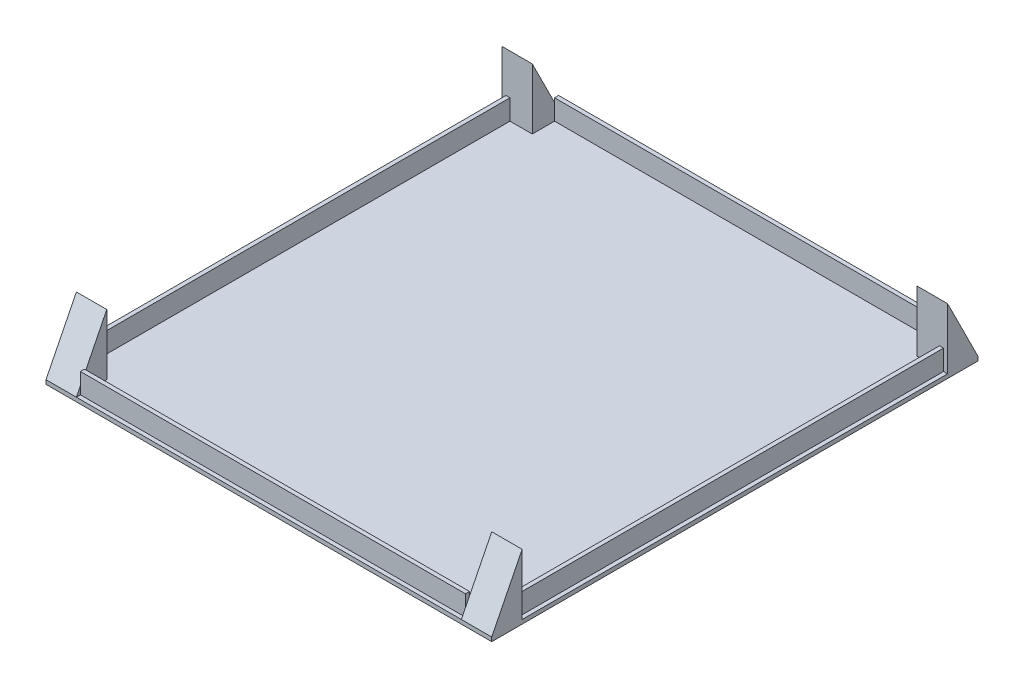
SolidWorks part; units mm, degrees
ref_plane "Front Plane" through (0, 0, 0) normal (0, 0, 1) x (1, 0, 0)
ref_plane "Top Plane" through (0, 0, 0) normal (0, 1, 0) x (1, 0, 0)
ref_plane "Right Plane" through (0, 0, 0) normal (1, 0, 0) x (0, 0, -1)
sketch "Sketch2" plane through (0, 0, 0) normal (0, 1, 0) x (1, 0, 0)
  line L1 (-110, 120) -> (110, 120)
  line L2 (-110, 120) -> (-110, -120)
  line L3 (-110, -120) -> (110, -120)
  line L4 (110, 120) -> (110, -120)
  line L5 (-110, 120) -> (110, -120) construction
  line L6 (-110, -120) -> (110, 120) construction
  point P0 (0, 0)
  dimension "D1" = 220
  dimension "D2" = 240
extrude "Boss-Extrude1" add sketch "Sketch2" along normal blind 2 contours L1 L4 L3 L2
sketch "Sketch4" plane through (0, 2, 0) normal (0, 1, 0) x (1, 0, 0)
  line L0 (-95, 120) -> (-95, 118) construction
  line L2 (-95, 118) -> (95, 118)
  line L4 (-95, 118) -> (-95, 116)
  line L5 (-95, 116) -> (95, 116)
  line L6 (95, 116) -> (95, 118)
  line L7 (-108, -105) -> (-108, 105)
  line L8 (95, -120) -> (95, -118) construction
  line L9 (95, -118) -> (-95, -118)
  line L10 (95, -118) -> (95, -116)
  line L11 (95, -116) -> (-95, -116)
  line L12 (-95, -116) -> (-95, -118)
  line L13 (-108, 105) -> (-106, 105)
  line L18 (-110, -105) -> (-108, -105) construction
  line L20 (-108, -105) -> (-106, -105)
  line L22 (-106, -105) -> (-106, 105)
  line L26 (108, 105) -> (108, -105)
  line L29 (108, -105) -> (106, -105)
  line L30 (110, 105) -> (108, 105) construction
  line L31 (108, 105) -> (106, 105)
  line L32 (106, 105) -> (106, -105)
  dimension "D1" = 2
  dimension "D2" = 2
  dimension "D3" = 2
  dimension "D4" = 2
  dimension "D5" = 2
extrude "Boss-Extrude3" add sketch "Sketch4" along normal blind 10
sketch "Sketch5" plane through (110, 0, 0) normal (1, 0, 0) x (0, 0, -1)
  line L0 (-120, 2) -> (-105, 2)
  line L1 (-105, 2) -> (-105, 32)
  line L2 (-105, 32) -> (-120, 2)
  line L3 (120, 2) -> (105, 2)
  line L4 (105, 2) -> (105, 32)
  line L5 (105, 32) -> (120, 2)
  dimension "D1" = 30
  dimension "D2" = 30
extrude "Boss-Extrude4" add sketch "Sketch5" against normal blind 15
sketch "Sketch6" plane through (-110, 0, 0) normal (-1, 0, 0) x (0, 0, 1)
  line L0 (120, 2) -> (105, 2)
  line L1 (105, 2) -> (105, 32)
  line L2 (105, 2) -> (105, 32) construction
  line L3 (105, 32) -> (116, 10) construction
  line L4 (105, 32) -> (120, 2)
  line L5 (-105, 32) -> (-105, 2)
  line L6 (-105, 2) -> (-120, 2)
  line L7 (-120, 2) -> (-105, 32)
extrude "Boss-Extrude5" add sketch "Sketch6" against normal blind 15
